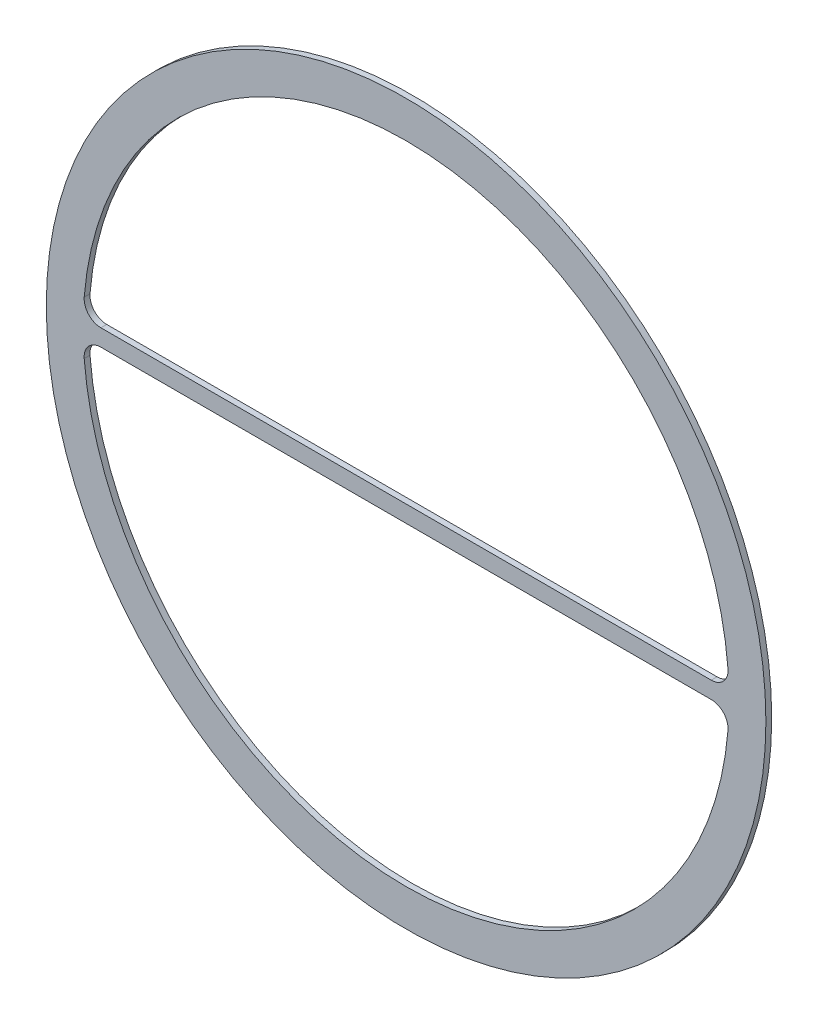
SolidWorks part; units mm, degrees
ref_plane "Front Plane" through (0, 0, 0) normal (0, 0, 1) x (1, 0, 0)
ref_plane "Top Plane" through (0, 0, 0) normal (0, 1, 0) x (1, 0, 0)
ref_plane "Right Plane" through (0, 0, 0) normal (1, 0, 0) x (0, 0, -1)
sketch "Sketch1" plane through (0, 0, 0) normal (0, 0, 1) x (1, 0, 0)
  line L0 (-147.17, 0) -> (128.0725, 0) construction
  line L1 (-249.9155, 6.5) -> (249.9155, 6.5)
  line L3 (-249.9155, -6.5) -> (249.9155, -6.5)
  line L5 (-249.9214, 6.2697) -> (249.9214, -6.2697) construction
  line L6 (-249.9214, -6.2697) -> (249.9214, 6.2697) construction
  arc A0 (-249.9214, -6.2697) -> (249.9214, -6.2697) centre (0, 0) ccw
  circle A1 centre (0, 0) radius 278.5
  arc A2 (249.9214, 6.2697) -> (-249.9214, 6.2697) centre (0, 0) ccw
  dimension "D1" = 500
  dimension "D2" = 557
  dimension "D3" = 13
extrude "Boss-Extrude2" add sketch "Sketch1" along normal blind 4.5
fillet "Fillet1" radius 13 4 edges at (-249.9155, -6.5, 2.25) (249.9155, -6.5, 2.25) (-249.9155, 6.5, 2.25) (249.9155, 6.5, 2.25)
